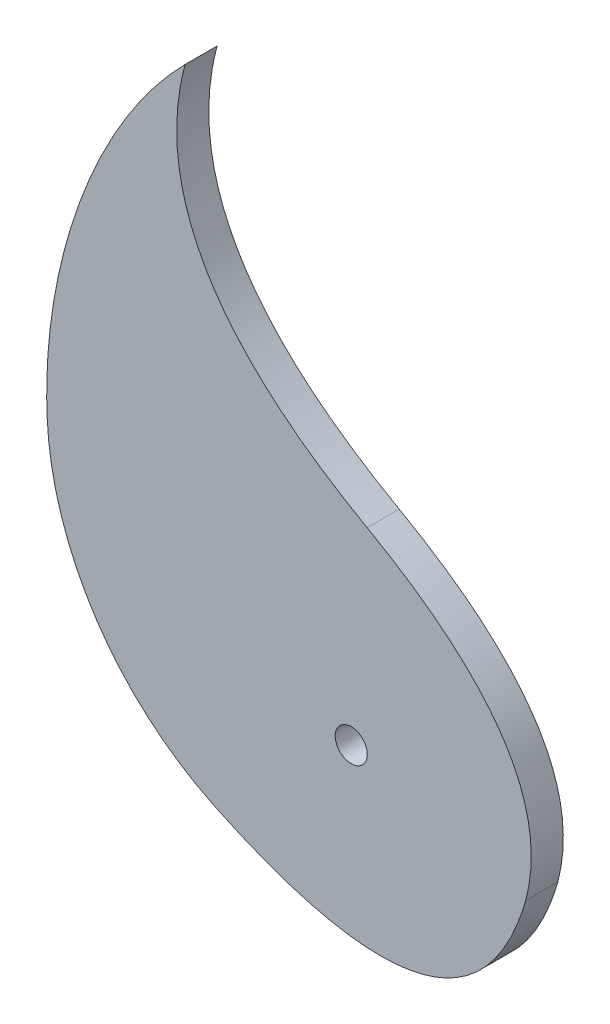
SolidWorks part; units mm, degrees
ref_plane "Front Plane" through (0, 0, 0) normal (0, 0, 1) x (1, 0, 0)
ref_plane "Top Plane" through (0, 0, 0) normal (0, 1, 0) x (1, 0, 0)
ref_plane "Right Plane" through (0, 0, 0) normal (1, 0, 0) x (0, 0, -1)
sketch "Sketch1" plane through (0, 0, 0) normal (0, 0, 1) x (1, 0, 0)
  spline S0 degree 2 poles (0, 0) (-45.5753, 25.6109) (-36.0604, 61.3837) knots 0 0 0 1 1 1
  spline S1 degree 3 poles (-36.0604, 61.3837) (-62.6153, 34.5944) (-74.1164, -18.8708) (-51.0518, -51.2544) knots 0 0 0 0 1 1 1 1
  spline S2 degree 2 poles (-51.0518, -51.2544) (17.9718, -94.4029) (31.4009, -48.2156) knots 0 0 0 1 1 1
  spline S3 degree 2 poles (0, 0) (43.5745, -24.5078) (28.6921, -55.4732) knots 0 0 0 1 1 1
extrude "Boss-Extrude1" add sketch "Sketch1" along normal blind 6.35 contours S3 S0 S1 S2
sketch "Sketch2" plane through (0, 0, 6.35) normal (0, 0, 1) x (1, 0, 0)
  circle A0 centre (-3.1525, -38.8714) radius 3.175
extrude "Cut-Extrude1" cut sketch "Sketch2" against normal blind 76.2
fillet "Fillet1" radius 58.42 3 edges at (-51.0518, -51.2544, 3.175)
